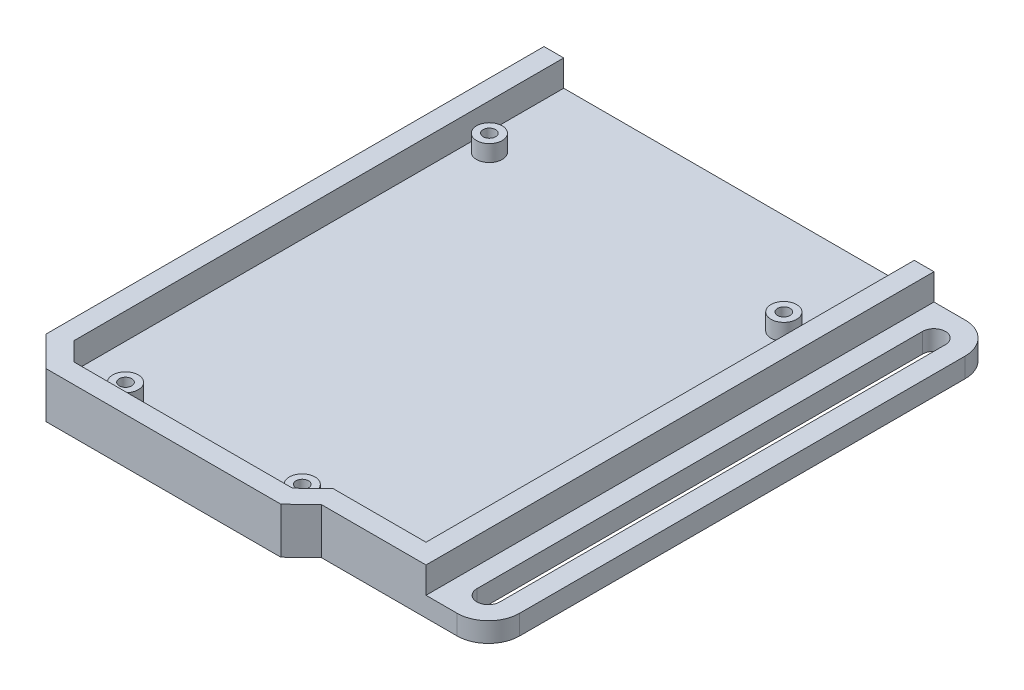
SolidWorks part; units mm, degrees
ref_plane "Alzado" through (0, 0, 0) normal (0, 0, 1) x (1, 0, 0)
ref_plane "Planta" through (0, 0, 0) normal (0, 1, 0) x (1, 0, 0)
ref_plane "Vista lateral" through (0, 0, 0) normal (1, 0, 0) x (0, 0, -1)
sketch "Croquis2" plane through (0, 0, 0) normal (0, 1, 0) x (1, 0, 0)
  point P0 (0, 0)
  point P29 (59.391, -38.6829)
  line B0 (0, 0) -> (0, -75.8499)
  line B1 (0, -75.8499) -> (4.5503, -80.4002)
  line B2 (4.5503, -80.4002) -> (40.3108, -80.4002)
  line B3 (40.3108, -80.4002) -> (43.4662, -77.3657)
  line B4 (43.4662, -77.3657) -> (59.391, -77.3657)
  line B5 (59.391, -77.3657) -> (59.391, 0)
  line B6 (56.391, 0) -> (3, 0)
  line B7 (3, 0) -> (3, -74.6073)
  line B8 (3, -74.6073) -> (5.7929, -77.4002)
  line B9 (5.7929, -77.4002) -> (39.1024, -77.4002)
  line B10 (39.1024, -77.4002) -> (42.2577, -74.3657)
  line B11 (42.2577, -74.3657) -> (56.391, -74.3657)
  line B12 (56.391, -74.3657) -> (56.391, 0)
  line B13 (0, 0) -> (59.391, 0)
  line B14 (59.391, 0) -> (64.141, 0)
  line B15 (59.391, -77.3657) -> (64.141, -77.3657)
  line B16 (68.891, -4.75) -> (68.891, -72.6157)
  line B17 (59.391, -4.75) -> (59.391, -72.6157)
  circle B18 centre (37.827, -74.6532) radius 0.95
  circle B19 centre (10.9124, -74.6532) radius 0.95
  circle B20 centre (51.7624, -15.2409) radius 0.95
  circle B21 centre (5.7667, -14.0885) radius 0.95
  arc B22 (59.391, -72.6157) -> (68.891, -72.6157) centre (64.141, -72.6157) ccw
  arc B23 (68.891, -4.75) -> (59.391, -4.75) centre (64.141, -4.75) ccw
  line B24 (64.141, -4.75) -> (64.141, -72.6157) construction
  line B25 (65.891, -4.75) -> (65.891, -72.6157)
  line B26 (62.391, -4.75) -> (62.391, -72.6157)
  arc B27 (65.891, -4.75) -> (62.391, -4.75) centre (64.141, -4.75) ccw
  arc B28 (62.391, -72.6157) -> (65.891, -72.6157) centre (64.141, -72.6157) ccw
sketch_block_instance "Bloque1-1"
sketch_block "Bloque1"
extrude "Saliente-Extruir1" add sketch "Croquis2" along normal blind 3 contours B11 B12 B6 B7 B8 B9 B10 B21 B20 B19 B18 | B13 B0 B1 B2 B3 B4 B5 B12 B11 B10 B9 B8 B7 | B21 | B18 | B16 B23 B5 B22 B28 B26 B27 B25 | B20 | B19 | B22 B5 B15 | B23 B14 B5
sketch "Croquis4" plane through (0, 3, 0) normal (0, 1, 0) x (1, 0, 0)
  line L0 (0, 0) -> (0, -75.8499)
  line L1 (0, -75.8499) -> (4.5503, -80.4002)
  line L2 (4.5503, -80.4002) -> (40.3108, -80.4002)
  line L3 (40.3108, -80.4002) -> (43.4662, -77.3657)
  line L4 (43.4662, -77.3657) -> (59.391, -77.3657)
  line L5 (59.391, -77.3657) -> (59.391, 0)
  line L7 (3, 0) -> (3, -74.6073)
  line L8 (3, -74.6073) -> (5.7929, -77.4002)
  line L9 (5.7929, -77.4002) -> (39.1024, -77.4002)
  line L10 (39.1024, -77.4002) -> (42.2577, -74.3657)
  line L11 (42.2577, -74.3657) -> (56.391, -74.3657)
  line L12 (56.391, -74.3657) -> (56.391, 0)
  line L13 (59.391, 0) -> (56.391, 0)
  line L14 (0, 0) -> (3, 0)
  dimension "D1" = 3
extrude "Saliente-Extruir2" add sketch "Croquis4" along normal blind 4
sketch "Croquis5" plane through (0, 3, 0) normal (0, 1, 0) x (1, 0, 0)
  circle A0 centre (51.7624, -15.2409) radius 0.95 construction
  circle A1 centre (37.827, -74.6532) radius 0.95 construction
  circle A2 centre (10.9124, -74.6532) radius 0.95 construction
  circle A3 centre (5.7667, -14.0885) radius 0.95 construction
  circle A4 centre (51.7624, -15.2409) radius 0.95
  circle A5 centre (37.827, -74.6532) radius 0.95
  circle A6 centre (10.9124, -74.6532) radius 0.95
  circle A7 centre (5.7667, -14.0885) radius 0.95
  circle A8 centre (5.7667, -14.0885) radius 1.95
  circle A9 centre (51.7624, -15.2409) radius 1.95
  circle A10 centre (37.827, -74.6532) radius 1.95
  circle A11 centre (10.9124, -74.6532) radius 1.95
  dimension "D1" = 3.9
extrude "Saliente-Extruir3" add sketch "Croquis5" along normal blind 2.5
